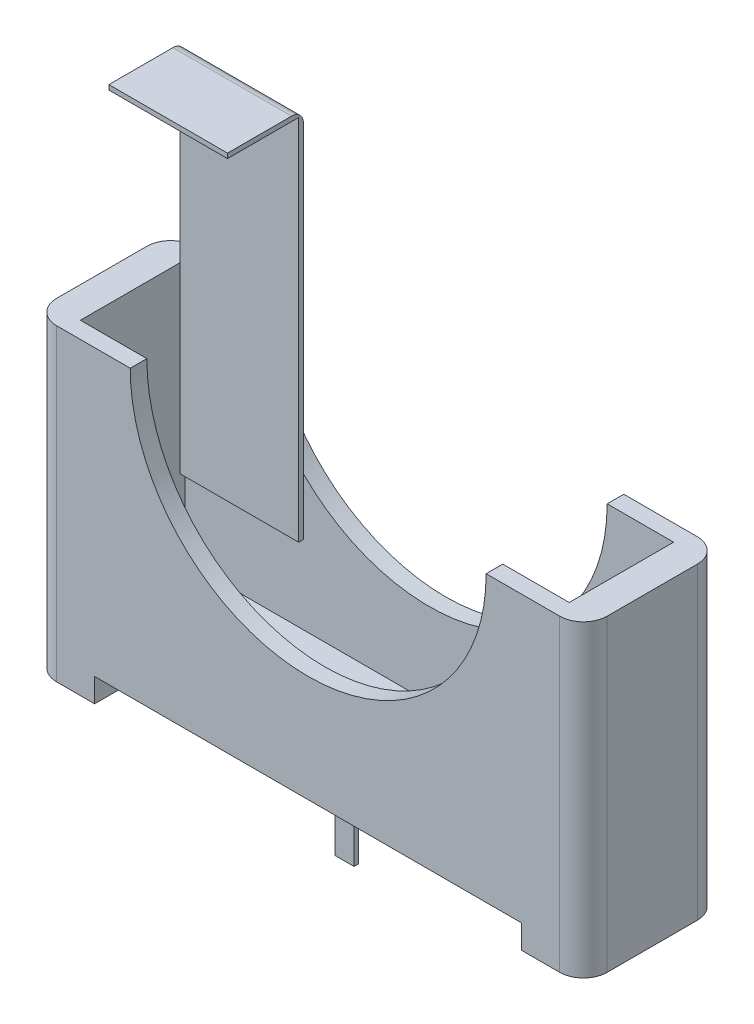
SolidWorks part; units mm, degrees
ref_plane "Front Plane" through (0, 0, 0) normal (0, 0, 1) x (1, 0, 0)
ref_plane "Top Plane" through (0, 0, 0) normal (0, 1, 0) x (1, 0, 0)
ref_plane "Right Plane" through (0, 0, 0) normal (1, 0, 0) x (0, 0, -1)
sketch "Sketch1" plane through (0, 0, 0) normal (0, 1, 0) x (1, 0, 0)
  line L1 (-11.6, 2.9) -> (11.6, 2.9)
  line L2 (-11.6, 2.9) -> (-11.6, -2.9)
  line L3 (-11.6, -2.9) -> (11.6, -2.9)
  line L4 (11.6, 2.9) -> (11.6, -2.9)
  line L5 (-11.6, 2.9) -> (11.6, -2.9) construction
  line L6 (-11.6, -2.9) -> (11.6, 2.9) construction
  point P0 (0, 0)
  dimension "D1" = 23.2
  dimension "D2" = 5.8
extrude "Boss-Extrude1" add sketch "Sketch1" along normal blind 13
sketch "Sketch2" plane through (0, 0, 2.9) normal (0, 0, 1) x (1, 0, 0)
  line L0 (0, 14.1733) -> (0, -3.025) construction
  line L1 (9, -4.6112) -> (-9, -4.6112)
  line L2 (9, -4.6112) -> (9, 1)
  line L3 (9, 1) -> (-9, 1)
  line L4 (-9, -4.6112) -> (-9, 1)
  line L5 (9, -4.6112) -> (-9, 1) construction
  line L6 (9, 1) -> (-9, -4.6112) construction
  line L7 (-11.6, 0) -> (11.6, 0) construction
  line L8 (-11.6, 13) -> (11.6, 13) construction
  circle A0 centre (0, 13) radius 7.5
  point P0 (0, -1.8056)
  dimension "D3" = 15
  dimension "D1" = 18
  dimension "D2" = 1
extrude "Cut-Extrude1" cut sketch "Sketch2" against normal through all
sketch "Sketch3" plane through (0, 13, 0) normal (0, 1, 0) x (1, 0, 0)
  line L0 (-11.6, 2.9) -> (-11.6, -2.9) construction
  line L1 (-10.3, 2.2) -> (10.3, 2.2)
  line L2 (-10.3, 2.2) -> (-10.3, -2.2)
  line L3 (-10.3, -2.2) -> (10.3, -2.2)
  line L4 (10.3, 2.2) -> (10.3, -2.2)
  line L5 (-10.3, 2.2) -> (10.3, -2.2) construction
  line L6 (-10.3, -2.2) -> (10.3, 2.2) construction
  line L7 (-11.6, -2.9) -> (-7.5, -2.9) construction
  point P0 (0, 0)
  dimension "D1" = 1.3
  dimension "D2" = 0.7
extrude "Cut-Extrude2" cut sketch "Sketch3" against normal blind 11
sketch "Sketch4" plane through (0, 1, 0) normal (0, -1, 0) x (1, 0, 0)
  line L0 (-14.6733, 0) -> (14.1963, 0) construction
  line L1 (-13.9157, 1.27) -> (14.1963, 1.27) construction
  line L2 (-13.9157, -1.27) -> (14.028, -1.27) construction
  line L3 (0, 3.8857) -> (0, -4.8677) construction
  line L4 (-5.08, 4.0789) -> (-5.08, -5.2394) construction
  line L5 (-0.4, 1.37) -> (0.4, 1.37)
  line L6 (-0.4, 1.37) -> (-0.4, 1.17)
  line L7 (-0.4, 1.17) -> (0.4, 1.17)
  line L8 (0.4, 1.37) -> (0.4, 1.17)
  line L9 (-0.4, 1.37) -> (0.4, 1.17) construction
  line L10 (-0.4, 1.17) -> (0.4, 1.37) construction
  line L11 (5.08, 4.0789) -> (5.08, -5.0324) construction
  line L13 (-5.48, -1.17) -> (-4.68, -1.17)
  line L14 (-5.48, -1.17) -> (-5.48, -1.37)
  line L15 (-5.48, -1.37) -> (-4.68, -1.37)
  line L16 (-4.68, -1.17) -> (-4.68, -1.37)
  line L17 (-5.48, -1.17) -> (-4.68, -1.37) construction
  line L18 (-5.48, -1.37) -> (-4.68, -1.17) construction
  line L19 (4.68, -1.17) -> (5.48, -1.17)
  line L20 (4.68, -1.17) -> (4.68, -1.37)
  line L21 (4.68, -1.37) -> (5.48, -1.37)
  line L22 (5.48, -1.17) -> (5.48, -1.37)
  line L23 (4.68, -1.17) -> (5.48, -1.37) construction
  line L24 (4.68, -1.37) -> (5.48, -1.17) construction
  point P9 (0, 1.27)
  point P18 (-5.08, -1.27)
  point P23 (5.08, -1.27)
  dimension "D1" = 2.54
  dimension "D2" = 0.8
  dimension "D3" = 0.2
  dimension "D4" = 5.08
  dimension "D5" = 5.08
extrude "Boss-Extrude2" add sketch "Sketch4" along normal blind 3
fillet "Fillet1" radius 1 4 edges at (-11.6, 6.5, -2.9) (11.6, 6.5, -2.9) (11.6, 6.5, 2.9) (-11.6, 6.5, 2.9)
sketch "Sketch5" plane through (0, 0, -2.2) normal (0, 0, 1) x (1, 0, 0)
  line L0 (-10.3, 21) -> (-5.3, 21)
  line L1 (-5.3, 21) -> (-5.3, 5.2972)
  line L2 (-5.3, 5.2972) -> (-10.3, 5.2972)
  line L3 (-10.3, 5.2972) -> (-10.3, 21)
  line L4 (-10.6, 13) -> (-7.5, 13) construction
  line L5 (-10.3, 2) -> (-10.3, 13) construction
  dimension "D1" = 5
  dimension "D2" = 8
extrude "Boss-Extrude3" add sketch "Sketch5" along normal blind 0.2
sketch "Sketch6" plane through (0, 0, -2) normal (0, 0, 1) x (1, 0, 0)
  line L0 (-5.3, 5.2972) -> (-5.3, 21) construction
  line L1 (-10.3, 21) -> (-5.3, 21)
  line L2 (-10.3, 21) -> (-10.3, 20.8)
  line L3 (-10.3, 20.8) -> (-5.3, 20.8)
  line L4 (-5.3, 21) -> (-5.3, 20.8)
  dimension "D1" = 0.2
extrude "Boss-Extrude4" add sketch "Sketch6" along normal blind 3
fillet "Fillet2" radius 0.5 1 edges at (-7.8, 21, -2.2)
